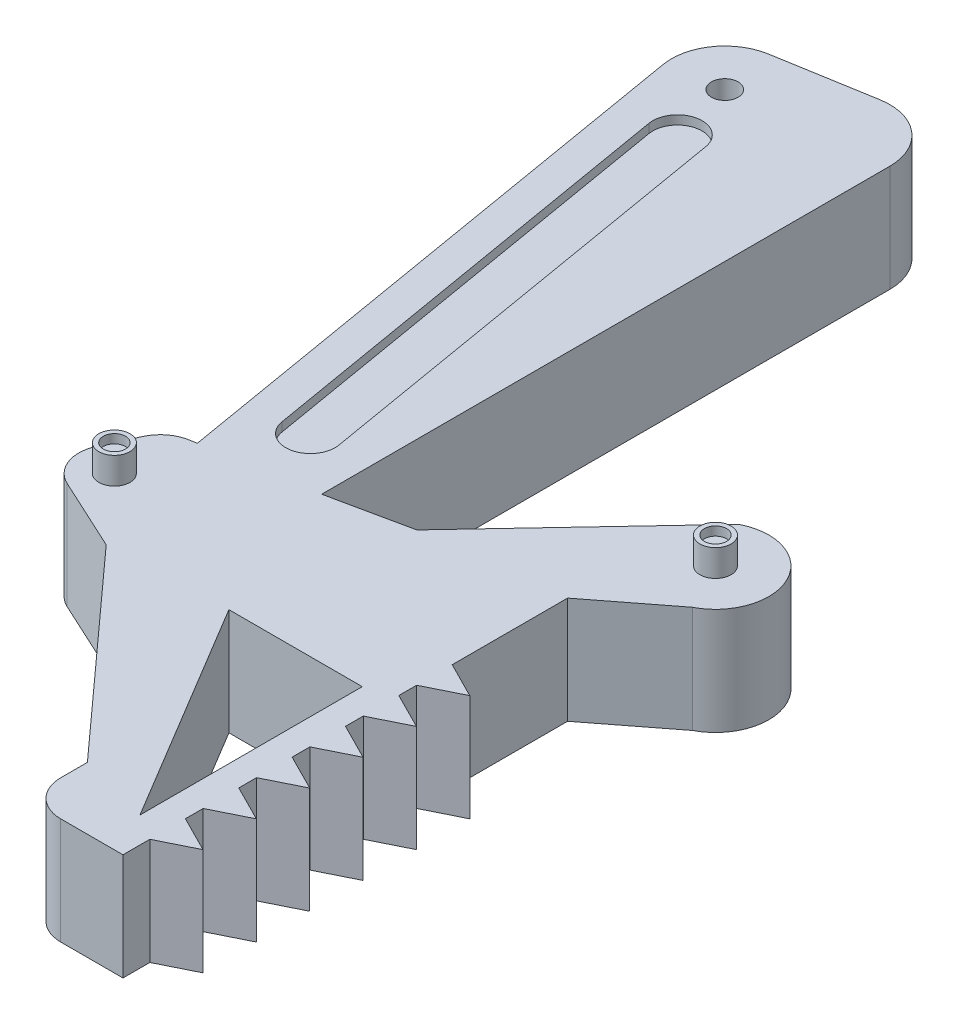
SolidWorks part; units mm, degrees
ref_plane "Front Plane" through (0, 0, 0) normal (0, 0, 1) x (1, 0, 0)
ref_plane "Top Plane" through (0, 0, 0) normal (0, 1, 0) x (1, 0, 0)
ref_plane "Right Plane" through (0, 0, 0) normal (1, 0, 0) x (0, 0, -1)
sketch "Sketch1" plane through (0, 0, 0) normal (0, 1, 0) x (1, 0, 0)
  line L0 (0, 0) -> (-59.8833, 0) construction
  line L1 (-12.9415, 0) -> (-36.6035, -4.0139)
  line L2 (-36.6035, -4.0139) -> (-24.8964, -73.0279)
  line L3 (-12.9415, 0) -> (-12.9415, -71)
  line L4 (-12.9415, -71) -> (-24.8964, -73.0279)
  line L5 (-24.8964, -73.0279) -> (-27.7303, -73.5087)
  line L6 (-27.7303, -73.5087) -> (-31.9284, -82.5848)
  line L7 (-31.9284, -82.5848) -> (-20.1294, -88.0423)
  line L8 (-20.1294, -88.0423) -> (0, -110.2866)
  line L9 (0, -110.2866) -> (0, -117.2866)
  line L10 (0, -117.2866) -> (11, -117.2866)
  line L11 (11, -117.2866) -> (11, -67.2866)
  line L12 (11, -67.2866) -> (18.908, -61.1658)
  line L13 (-12.9415, -71) -> (-4.1071, -69.1261)
  line L14 (-4.1071, -69.1261) -> (13.4322, -50.4879)
  arc A0 (13.4322, -50.4879) -> (18.908, -61.1658) centre (16.1701, -55.8268) cw
  dimension "D12" = 6
  dimension "D1" = 70
  dimension "D2" = 71
  dimension "D3" = 24
  dimension "D4" = 15
  dimension "D5" = 10
  dimension "D6" = 13
  dimension "D7" = 30
  dimension "D8" = 7
  dimension "D9" = 11
  dimension "D10" = 50
  dimension "D11" = 10
extrude "Boss-Extrude1" add sketch "Sketch1" along normal mid plane 12 contours A0 L14 L13 L4 L5 L6 L7 L8 L9 L10 L11 L12 | L4 L3 L1 L2
fillet "Fillet1" radius 6 2 edges at (-12.9415, 0, 0) (-36.6035, 0, 4.0139)
fillet "Fillet2" radius 4 3 edges at (0, 0, 117.2866) (-31.9284, 0, 82.5848) (-27.7303, 0, 73.5087)
sketch "Sketch2" plane through (0, 6, 0) normal (0, 1, 0) x (1, 0, 0)
  line L0 (11, -117.2866) -> (11, -112.2866) construction
  line L1 (11, -117.2866) -> (11, -67.2866) construction
  line L2 (11, -112.2866) -> (15, -112.2866) construction
  line L3 (15, -112.2866) -> (11, -114.2656)
  line L4 (11, -114.2656) -> (11, -110.2656)
  line L5 (11, -110.2656) -> (15, -112.2866)
  dimension "D1" = 5
  dimension "D2" = 4
  dimension "D3" = 4
extrude "Boss-Extrude2" add sketch "Sketch2" against normal blind 12
pattern_linear "LPattern1" count 6 spacing 6 along (0, 0, -1) of "Boss-Extrude2"
sketch "Sketch3" plane through (0, 6, 0) normal (0, 1, 0) x (1, 0, 0)
  line L0 (8.0829, -112.4576) -> (8.0829, -87.4576)
  line L1 (8.0829, -87.4576) -> (-6.9171, -87.4576)
  line L2 (-6.9171, -87.4576) -> (8.0829, -112.4576)
  dimension "D1" = 15
  dimension "D2" = 25
extrude "Cut-Extrude1" cut sketch "Sketch3" against normal blind 26
sketch "Sketch5" plane through (0, 6, 0) normal (0, 1, 0) x (1, 0, 0)
  circle A0 centre (-29.6846, -8.9259) radius 1.5
  dimension "D1" = 3
extrude "Cut-Extrude4" cut sketch "Sketch5" against normal through all
sketch "Sketch6" plane through (0, 6, 0) normal (0, 1, 0) x (1, 0, 0)
  circle A0 centre (-26.6187, -80.6336) radius 1.75
  circle A1 centre (16.1701, -55.8268) radius 1.75
  dimension "D1" = 3.5
  dimension "D2" = 3.5
extrude "Boss-Extrude3" add sketch "Sketch6" along normal blind 3
sketch "Sketch7" plane through (0, 9, 0) normal (0, 1, 0) x (1, 0, 0)
  circle A2 centre (-26.6187, -80.6336) radius 1.25
  circle A3 centre (-26.6187, -80.6336) radius 1.25
  dimension "D1" = 0.5
extrude "Cut-Extrude6" cut sketch "Sketch7" against normal blind 1
sketch "Sketch8" plane through (0, 9, 0) normal (0, 1, 0) x (1, 0, 0)
  circle A2 centre (16.1701, -55.8268) radius 1.25
  circle A3 centre (16.1701, -55.8268) radius 1.25
  dimension "D1" = 0.5
extrude "Cut-Extrude7" cut sketch "Sketch8" against normal blind 1
sketch "Sketch9" plane through (0, 6, 0) normal (0, 1, 0) x (1, 0, 0)
  line L0 (-27.9308, -16.0041) -> (-19.492, -65.7159) construction
  line L1 (-25.1962, -15.5399) -> (-16.7575, -65.2517)
  line L2 (-30.6654, -16.4683) -> (-22.2266, -66.1801)
  arc A0 (-25.1962, -15.5399) -> (-30.6654, -16.4683) centre (-27.9308, -16.0041) ccw
  arc A1 (-22.2266, -66.1801) -> (-16.7575, -65.2517) centre (-19.492, -65.7159) ccw
  point P2 (-23.7114, -40.86)
extrude "Cut-Extrude8" cut sketch "Sketch9" against normal blind 1 contours L2 A1 L1 A0
mirror "Mirror1" about plane through (0, 0, 0) normal (0, 1, 0) of "Cut-Extrude8", "Boss-Extrude3"
